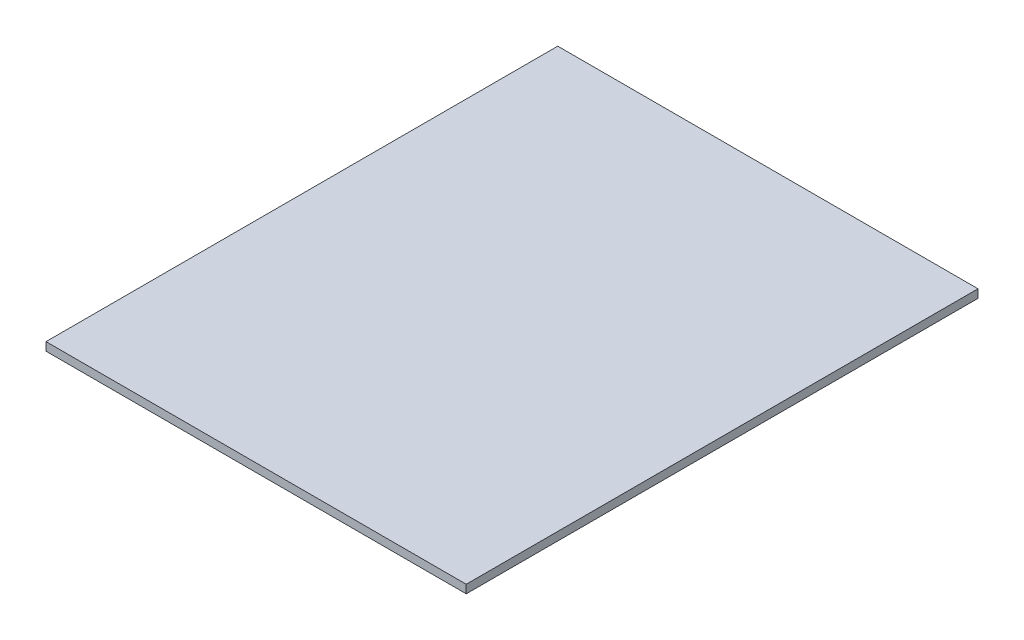
SolidWorks part; units mm, degrees
ref_plane "Front Plane" through (0, 0, 0) normal (0, 0, 1) x (1, 0, 0)
ref_plane "Top Plane" through (0, 0, 0) normal (0, 1, 0) x (1, 0, 0)
ref_plane "Right Plane" through (0, 0, 0) normal (1, 0, 0) x (0, 0, -1)
sketch "Sketch1" plane through (0, 0, 0) normal (0, 1, 0) x (1, 0, 0)
  line L1 (0, 0) -> (404, 0)
  line L2 (0, 0) -> (0, -492)
  line L3 (0, -492) -> (404, -492)
  line L4 (404, 0) -> (404, -492)
  dimension "D1" = 492
  dimension "D2" = 404
extrude "Boss-Extrude3" add sketch "Sketch1" along normal blind 8 contours L2 L3 L4 L1
